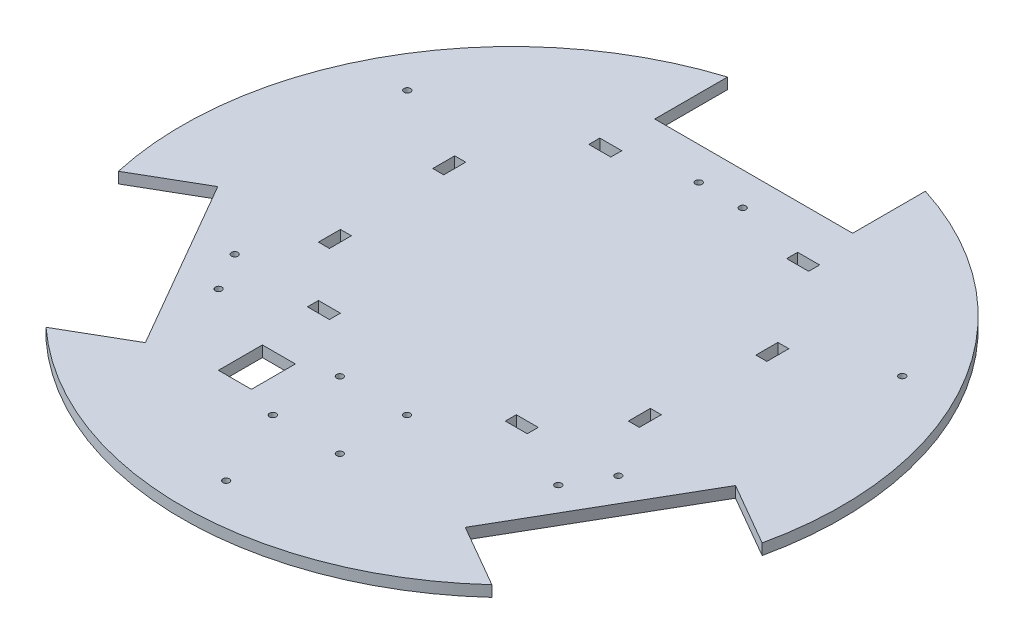
SolidWorks part; units mm, degrees
ref_plane "Front Plane" through (0, 0, 0) normal (0, 0, 1) x (1, 0, 0)
ref_plane "Top Plane" through (0, 0, 0) normal (0, 1, 0) x (1, 0, 0)
ref_plane "Right Plane" through (0, 0, 0) normal (1, 0, 0) x (0, 0, -1)
sketch "Sketch1" plane through (0, 0, 0) normal (0, 1, 0) x (1, 0, 0)
  line L0 (0, 0) -> (0, 110) construction
  line L1 (0, 0) -> (95.2628, -55) construction
  line L2 (0, 0) -> (-95.2628, -55) construction
  line L3 (-45, 110) -> (45, 110)
  line L4 (-117.7628, -16.0289) -> (-72.7628, -93.9711)
  line L5 (72.7628, -93.9711) -> (117.7628, -16.0289)
  line L6 (-45, 110) -> (-45, 143.0909)
  line L7 (45, 110) -> (45, 143.0909)
  line L8 (-117.7628, -16.0289) -> (-146.4203, -32.5743)
  line L9 (-72.7628, -93.9711) -> (-101.4203, -110.5166)
  line L10 (117.7628, -16.0289) -> (146.4203, -32.5743)
  line L11 (72.7628, -93.9711) -> (101.4203, -110.5166)
  arc A0 (-101.4203, -110.5166) -> (101.4203, -110.5166) centre (0, 0) ccw
  arc A1 (146.4203, -32.5743) -> (45, 143.0909) centre (0, 0) ccw
  arc A2 (-45, 143.0909) -> (-146.4203, -32.5743) centre (0, 0) ccw
  point P6 (0, 110)
  point P9 (0, 0)
  point P14 (-95.2628, -55)
  point P15 (95.2628, -55)
  dimension "D1" = 300
  dimension "D2" = 110
  dimension "D3" = 3
  dimension "D4" = 90
extrude "Boss-Extrude1" add sketch "Sketch1" along normal blind 5
sketch "Sketch2" plane through (0, 5, 0) normal (0, 1, 0) x (1, 0, 0)
  line L0 (-10, 95) -> (10, 95) construction
  line L1 (45, 110) -> (-45, 110) construction
  line L2 (-87.2724, -38.8397) -> (-77.2724, -56.1603) construction
  line L3 (77.2724, -56.1603) -> (87.2724, -38.8397) construction
  line L4 (-117.7628, -16.0289) -> (-72.7628, -93.9711) construction
  line L7 (-95.2628, -55) -> (-82.2724, -47.5) construction
  line L8 (95.2628, -55) -> (82.2724, -47.5) construction
  line L9 (72.7628, -93.9711) -> (117.7628, -16.0289) construction
  circle A0 centre (-10, 95) radius 1.5
  circle A1 centre (10, 95) radius 1.5
  circle A2 centre (-87.2724, -38.8397) radius 1.5
  circle A3 centre (-77.2724, -56.1603) radius 1.5
  circle A4 centre (77.2724, -56.1603) radius 1.5
  circle A5 centre (87.2724, -38.8397) radius 1.5
  point P4 (0, 95)
  point P7 (0, 110)
  dimension "D1" = 3
  dimension "D2" = 20
  dimension "D3" = 15
  dimension "D4" = 20
  dimension "D5" = 20
  dimension "D6" = 15
  dimension "D7" = 15
extrude "Cut-Extrude1" cut sketch "Sketch2" against normal blind 10
sketch "Sketch3" plane through (0, 5, 0) normal (0, 1, 0) x (1, 0, 0)
  line L0 (-70.5, -10) -> (70.5, -10) construction
  line L1 (40, 90) -> (50, 90)
  line L2 (40, 90) -> (40, 85)
  line L3 (40, 85) -> (50, 85)
  line L4 (50, 90) -> (50, 85)
  line L5 (40, 90) -> (50, 85) construction
  line L6 (40, 85) -> (50, 90) construction
  line L7 (-50, 90) -> (-40, 90)
  line L8 (-50, 90) -> (-50, 85)
  line L9 (-50, 85) -> (-40, 85)
  line L10 (-40, 90) -> (-40, 85)
  line L11 (-50, 90) -> (-40, 85) construction
  line L12 (-50, 85) -> (-40, 90) construction
  line L17 (-45, -40.5) -> (45, -40.5) construction
  line L25 (-76, 50) -> (-71, 50)
  line L26 (-76, 50) -> (-76, 40)
  line L27 (-76, 40) -> (-71, 40)
  line L28 (-71, 50) -> (-71, 40)
  line L29 (-76, 50) -> (-71, 40) construction
  line L30 (-76, 40) -> (-71, 50) construction
  line L31 (71, 50) -> (76, 50)
  line L32 (71, 50) -> (71, 40)
  line L33 (71, 40) -> (76, 40)
  line L34 (76, 50) -> (76, 40)
  line L35 (71, 50) -> (76, 40) construction
  line L36 (71, 40) -> (76, 50) construction
  line L38 (-50, -38) -> (-40, -38)
  line L39 (-50, -38) -> (-50, -43)
  line L40 (-50, -43) -> (-40, -43)
  line L41 (-40, -38) -> (-40, -43)
  line L42 (-50, -38) -> (-40, -43) construction
  line L43 (-50, -43) -> (-40, -38) construction
  line L44 (40, -38) -> (50, -38)
  line L45 (40, -38) -> (40, -43)
  line L46 (40, -43) -> (50, -43)
  line L47 (50, -38) -> (50, -43)
  line L48 (40, -38) -> (50, -43) construction
  line L49 (40, -43) -> (50, -38) construction
  line L50 (-73, -5) -> (-68, -5)
  line L51 (-73, -5) -> (-73, -15)
  line L52 (-73, -15) -> (-68, -15)
  line L53 (-68, -5) -> (-68, -15)
  line L54 (-73, -5) -> (-68, -15) construction
  line L55 (-73, -15) -> (-68, -5) construction
  line L56 (68, -5) -> (73, -5)
  line L57 (68, -5) -> (68, -15)
  line L58 (68, -15) -> (73, -15)
  line L59 (73, -5) -> (73, -15)
  line L60 (68, -5) -> (73, -15) construction
  line L61 (68, -15) -> (73, -5) construction
  circle A0 centre (-10, 95) radius 1.5 construction
  point P0 (45, 87.5)
  point P5 (-45, 87.5)
  point P14 (0, -40.5)
  point P24 (-73.5, 45)
  point P29 (73.5, 45)
  point P36 (0, -10)
  point P37 (-45, -40.5)
  point P42 (45, -40.5)
  point P47 (70.5, -10)
  point P48 (-70.5, -10)
  dimension "D1" = 10
  dimension "D2" = 5
  dimension "D3" = 90
  dimension "D4" = 5
  dimension "D5" = 5
  dimension "D6" = 71
  dimension "D7" = 10
  dimension "D8" = 40
  dimension "D9" = 142
  dimension "D10" = 123
  dimension "D11" = 5
  dimension "D12" = 10
  dimension "D13" = 136
  dimension "D14" = 55
extrude "Cut-Extrude2" cut sketch "Sketch3" against normal blind 10
sketch "Sketch4" plane through (0, 5, 0) normal (0, 1, 0) x (1, 0, 0)
  line L0 (-50, -43) -> (-40, -43) construction
  line L2 (-45.25, -68.25) -> (-30.25, -68.25)
  line L3 (-45.25, -68.25) -> (-45.25, -88.25)
  line L4 (-45.25, -88.25) -> (-30.25, -88.25)
  line L5 (-30.25, -68.25) -> (-30.25, -88.25)
  line L6 (-45.25, -68.25) -> (-30.25, -88.25) construction
  line L7 (-45.25, -88.25) -> (-30.25, -68.25) construction
  circle A0 centre (-15.25, -63) radius 1.5
  circle A1 centre (15.25, -63) radius 1.5
  circle A2 centre (-15.25, -93.5) radius 1.5
  circle A3 centre (15.25, -93.5) radius 1.5
  point P12 (-37.75, -78.25)
  dimension "D1" = 3
  dimension "D2" = 30.5
  dimension "D3" = 30.5
  dimension "D4" = 20
  dimension "D5" = 15.25
  dimension "D6" = 15
  dimension "D7" = 20
  dimension "D8" = 15.25
  dimension "D9" = 15
extrude "Cut-Extrude3" cut sketch "Sketch4" against normal blind 10
sketch "Sketch5" plane through (0, 5, 0) normal (0, 1, 0) x (1, 0, 0)
  line L0 (-112.5833, 65) -> (0, 0) construction
  line L1 (-129.9038, 75) -> (-112.5833, 65) construction
  circle A0 centre (-112.5833, 65) radius 1.5
  arc A1 (-45, 143.0909) -> (-146.4203, -32.5743) centre (0, 0) ccw construction
  circle A2 centre (112.5833, 65) radius 1.5
  circle A3 centre (0, -130) radius 1.5
  point P15 (0, 0)
  dimension "D1" = 3
  dimension "D2" = 130
  dimension "D3" = 20
  dimension "D4" = 3
extrude "Cut-Extrude4" cut sketch "Sketch5" against normal blind 10
